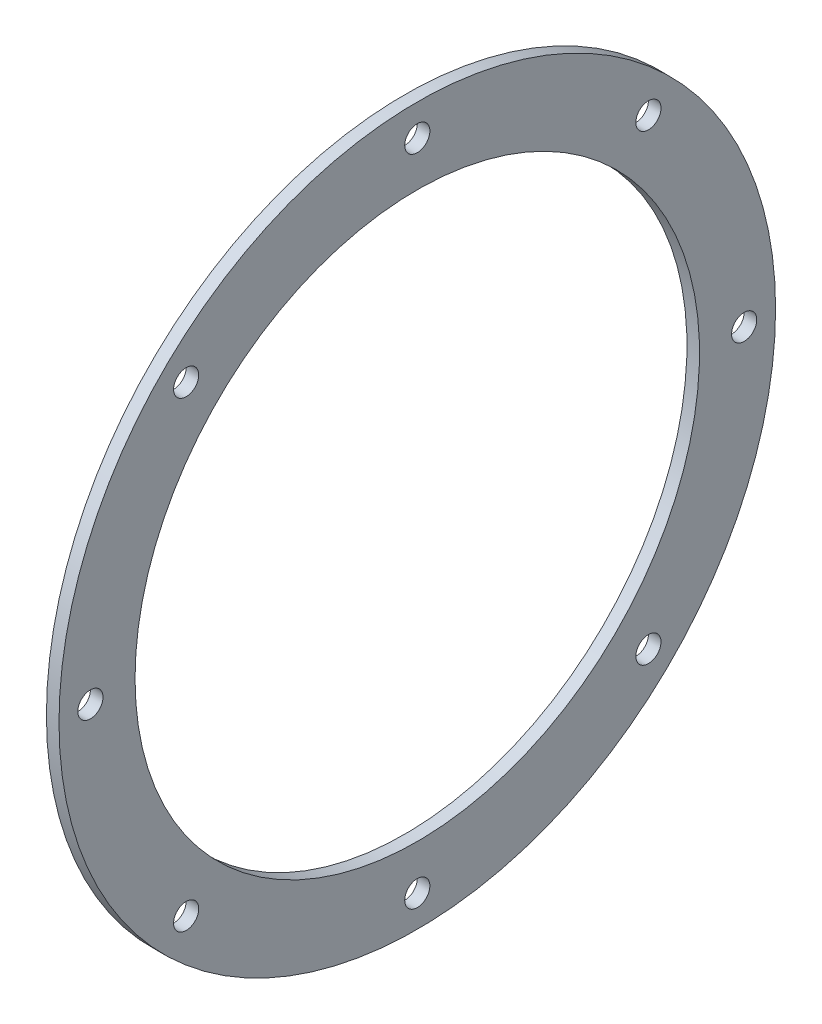
SolidWorks part; units mm, degrees
material "POLYURETHANE (11671)"
ref_plane "Front Plane" through (0, 0, 0) normal (0, 0, 1) x (1, 0, 0)
ref_plane "Top Plane" through (0, 0, 0) normal (0, 1, 0) x (1, 0, 0)
ref_plane "Right Plane" through (0, 0, 0) normal (1, 0, 0) x (0, 0, -1)
sketch "Sketch2" plane through (0, 0, 0) normal (0, 0, 1) x (1, 0, 0)
  line L0 (-478.1119, 0) -> (17585.1179, 0) construction
  line L3 (9.7498, 44.9) -> (11.7498, 44.9)
  line L9 (9.7498, 57) -> (11.7498, 57)
  line L10 (9.7498, 57) -> (9.7498, 44.9)
  line L11 (9.7498, 44.9) -> (11.7498, 44.9)
  line L12 (11.7498, 57) -> (11.7498, 44.9)
  point P1 (10.7498, 57)
  dimension "D1" = 44.9
  dimension "D2" = 57
  dimension "D8" = 2
revolve "Revolve1" add sketch "Sketch2" angle 360 about L0
sketch "Sketch3" plane through (9.7498, 0, 0) normal (-1, 0, 0) x (0, 0, 1)
  circle A2 centre (0, 52) radius 2
  dimension "D1" = 4
  dimension "D2" = 52
extrude "Cut-Extrude1" cut sketch "Sketch3" against normal blind 10
pattern_circular "CirPattern1" count 8 over 360 about axis through (0, 0, 0) along (1, 0, 0) of "Cut-Extrude1"
